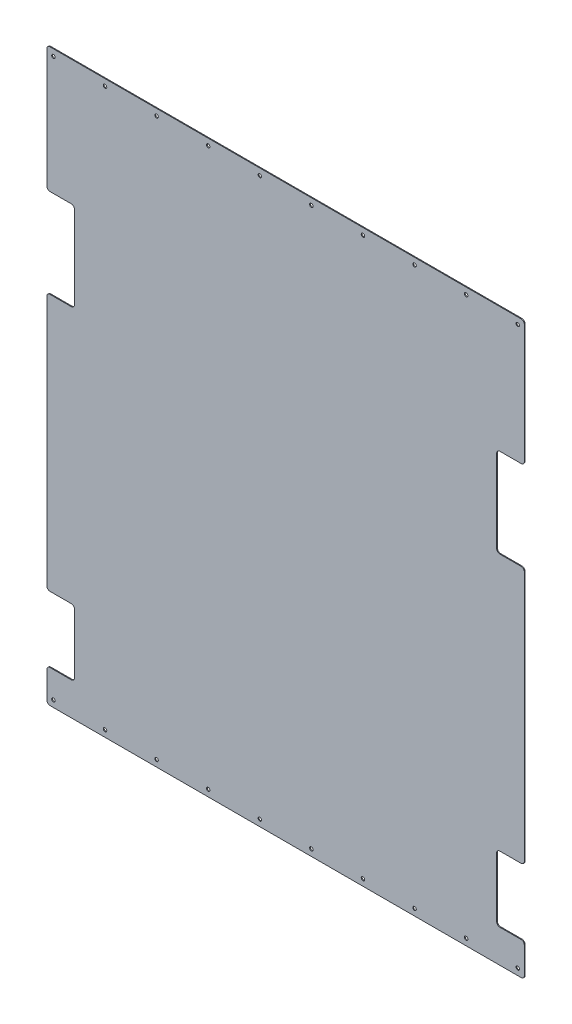
SolidWorks part; units mm, degrees
ref_plane "Front Plane" through (0, 0, 0) normal (0, 0, 1) x (1, 0, 0)
ref_plane "Top Plane" through (0, 0, 0) normal (0, 1, 0) x (1, 0, 0)
ref_plane "Right Plane" through (0, 0, 0) normal (1, 0, 0) x (0, 0, -1)
sketch "Sketch1" plane through (0, 0, 0) normal (0, 0, 1) x (1, 0, 0)
  line L1 (362, -432.5) -> (-362, -432.5)
  line L2 (362, -432.5) -> (362, 432.5)
  line L3 (362, 432.5) -> (-362, 432.5)
  line L4 (-362, -432.5) -> (-362, 432.5)
  line L5 (362, -432.5) -> (-362, 432.5) construction
  line L6 (362, 432.5) -> (-362, -432.5) construction
  point P0 (0, 0)
  dimension "D1" = 865
  dimension "D2" = 724
extrude "Boss-Extrude1" add sketch "Sketch1" along normal blind 1.27
sketch "Sketch2" plane through (0, 0, 1.27) normal (0, 0, 1) x (1, 0, 0)
  line L0 (-362, 432.5) -> (-362, -432.5) construction
  line L1 (-362, 242.5) -> (-320, 242.5)
  line L2 (-362, 242.5) -> (-362, 107.5)
  line L3 (-362, 107.5) -> (-320, 107.5)
  line L4 (-320, 242.5) -> (-320, 107.5)
  line L5 (362, 432.5) -> (-362, 432.5) construction
  line L6 (-362, -432.5) -> (362, -432.5) construction
  line L7 (-362, -382.5) -> (-320, -382.5)
  line L8 (-362, -382.5) -> (-362, -282.5)
  line L9 (-362, -282.5) -> (-320, -282.5)
  line L10 (-320, -382.5) -> (-320, -282.5)
  line L11 (362, -432.5) -> (362, 432.5) construction
  line L12 (362, 242.5) -> (320, 242.5)
  line L13 (362, 242.5) -> (362, 107.5)
  line L14 (362, 107.5) -> (320, 107.5)
  line L15 (320, 242.5) -> (320, 107.5)
  line L17 (362, -282.5) -> (320, -282.5)
  line L18 (362, -282.5) -> (362, -382.5)
  line L19 (362, -382.5) -> (320, -382.5)
  line L20 (320, -282.5) -> (320, -382.5)
  dimension "D1" = 190
  dimension "D2" = 42
  dimension "D3" = 135
  dimension "D4" = 50
  dimension "D5" = 42
  dimension "D6" = 100
  dimension "D7" = 135
  dimension "D8" = 42
  dimension "D9" = 42
  dimension "D10" = 100
extrude "Cut-Extrude1" cut sketch "Sketch2" against normal up to surface (1.27 mm away) up to face at (0, 0, 0)
sketch "Sketch3" plane through (0, 0, 1.27) normal (0, 0, 1) x (1, 0, 0)
  line L0 (362, 432.5) -> (-362, 432.5) construction
  line L1 (-362, 432.5) -> (-362, 242.5) construction
  line L2 (-362, -382.5) -> (-362, -432.5) construction
  line L3 (-362, -432.5) -> (362, -432.5) construction
  circle A0 centre (-352, 422.5) radius 2.65
  circle A1 centre (-352, -422.5) radius 2.65
  dimension "D1" = 5.3
  dimension "D6" = 5.3
  dimension "D2" = 10
  dimension "D3" = 10
  dimension "D4" = 10
  dimension "D5" = 10
extrude "Cut-Extrude2" cut sketch "Sketch3" against normal up to surface (1.27 mm away) up to face at (0, -63, 0)
pattern_linear "LPattern1" count 10 spacing 78.2222 along (1, 0, 0) of "Cut-Extrude2"
fillet "Fillet1" radius 5 20 edges at (-362, -432.5, 0.635) (362, -432.5, 0.635) (362, -382.5, 0.635) (320, -382.5, 0.635) (320, -282.5, 0.635) (362, -282.5, 0.635) (362, 107.5, 0.635) (320, 107.5, 0.635) (320, 242.5, 0.635) (362, 242.5, 0.635) (362, 432.5, 0.635) (-362, 432.5, 0.635) (-362, 242.5, 0.635) (-320, 242.5, 0.635) (-320, 107.5, 0.635) (-362, 107.5, 0.635) (-362, -282.5, 0.635) (-362, -382.5, 0.635) (-320, -382.5, 0.635) (-320, -282.5, 0.635)
